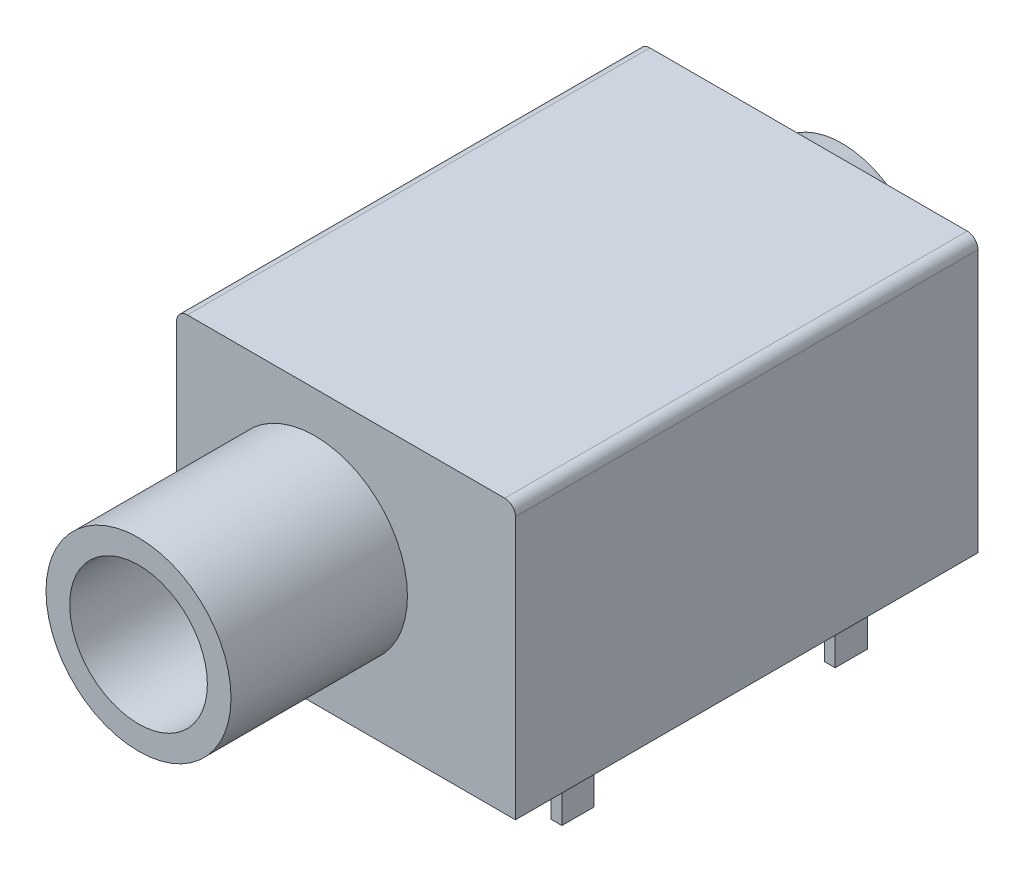
SolidWorks part; units mm, degrees
ref_plane "Front Plane" through (0, 0, 0) normal (0, 0, 1) x (1, 0, 0)
ref_plane "Top Plane" through (0, 0, 0) normal (0, 1, 0) x (1, 0, 0)
ref_plane "Right Plane" through (0, 0, 0) normal (1, 0, 0) x (0, 0, -1)
sketch "Sketch1" plane through (0, 0, 0) normal (0, 0, 1) x (1, 0, 0)
  line L1 (0, 0) -> (15.75, 0)
  line L2 (0, 0) -> (0, 12.2)
  line L3 (0.5, 12.7) -> (15.25, 12.7)
  line L4 (15.75, 0) -> (15.75, 12.2)
  arc A0 (15.25, 12.7) -> (15.75, 12.2) centre (15.25, 12.2) cw
  arc A1 (0, 12.2) -> (0.5, 12.7) centre (0.5, 12.2) cw
  point P7 (15.75, 12.7)
  dimension "D3" = 0.5
  dimension "D1" = 15.75
  dimension "D2" = 12.7
extrude "Boss-Extrude1" add sketch "Sketch1" against normal blind 21.5
sketch "Sketch2" plane through (0, 0, 0) normal (0, 0, 1) x (1, 0, 0)
  line L0 (0, 0) -> (15.75, 0) construction
  line L1 (0, 12.2) -> (0, 0) construction
  circle A0 centre (6.43, 6.5) radius 4.3
  dimension "D3" = 8.6
  dimension "D1" = 6.5
  dimension "D2" = 6.43
extrude "Boss-Extrude2" add sketch "Sketch2" along normal blind 8.2
sketch "Sketch7" plane through (0, 0, 8.2) normal (0, 0, 1) x (1, 0, 0)
  circle A0 centre (6.43, 6.5) radius 3.2
  point P3 (6.43, 6.5)
  dimension "D1" = 6.4
sketch "Sketch8" plane through (0, 0, -21.5) normal (0, 0, -1) x (-1, 0, 0)
  circle A0 centre (-6.43, 6.5) radius 4.3
  dimension "D1" = 8.6
extrude "Boss-Extrude3" add sketch "Sketch8" along normal blind 3 draft 9
extrude "Cut-Extrude1" cut sketch "Sketch7" against normal blind 31
sketch "Sketch9" plane through (0, 0, 0) normal (0, -1, 0) x (1, 0, 0)
  line L0 (6.43, 0) -> (6.43, -21.5) construction
  line L1 (0, 0) -> (15.75, 0) construction
  line L2 (0, -21.5) -> (15.75, -21.5) construction
  line L3 (0, -21.5) -> (0, 0) construction
  line L4 (2.23, -4.75) -> (13.66, -4.75) construction
  line L5 (1.98, -4) -> (2.48, -4)
  line L6 (1.98, -4) -> (1.98, -5.5)
  line L7 (1.98, -5.5) -> (2.48, -5.5)
  line L8 (2.48, -4) -> (2.48, -5.5)
  line L9 (1.98, -4) -> (2.48, -5.5) construction
  line L10 (1.98, -5.5) -> (2.48, -4) construction
  line L11 (13.41, -5.5) -> (13.91, -5.5)
  line L12 (13.41, -5.5) -> (13.41, -4)
  line L13 (13.41, -4) -> (13.91, -4)
  line L14 (13.91, -5.5) -> (13.91, -4)
  line L15 (13.41, -5.5) -> (13.91, -4) construction
  line L16 (13.41, -4) -> (13.91, -5.5) construction
  line L17 (2.23, -17.45) -> (13.66, -17.45) construction
  line L18 (1.98, -18.2) -> (2.48, -18.2)
  line L19 (1.98, -18.2) -> (1.98, -16.7)
  line L20 (1.98, -16.7) -> (2.48, -16.7)
  line L21 (2.48, -18.2) -> (2.48, -16.7)
  line L22 (1.98, -18.2) -> (2.48, -16.7) construction
  line L23 (1.98, -16.7) -> (2.48, -18.2) construction
  line L24 (13.41, -18.2) -> (13.91, -18.2)
  line L25 (13.41, -18.2) -> (13.41, -16.7)
  line L26 (13.41, -16.7) -> (13.91, -16.7)
  line L27 (13.91, -18.2) -> (13.91, -16.7)
  line L28 (13.41, -18.2) -> (13.91, -16.7) construction
  line L29 (13.41, -16.7) -> (13.91, -18.2) construction
  point P8 (2.23, -4.75)
  point P13 (13.66, -4.75)
  point P20 (2.23, -17.45)
  point P25 (13.66, -17.45)
  dimension "D1" = 6.43
  dimension "D2" = 4.2
  dimension "D3" = 11.43
  dimension "D4" = 4.75
  dimension "D5" = 17.45
  dimension "D6" = 4.2
  dimension "D7" = 11.43
  dimension "D8" = 1.98
  dimension "D9" = 4
  dimension "D12" = 15.75
extrude "Boss-Extrude4" add sketch "Sketch9" along normal blind 3.15
